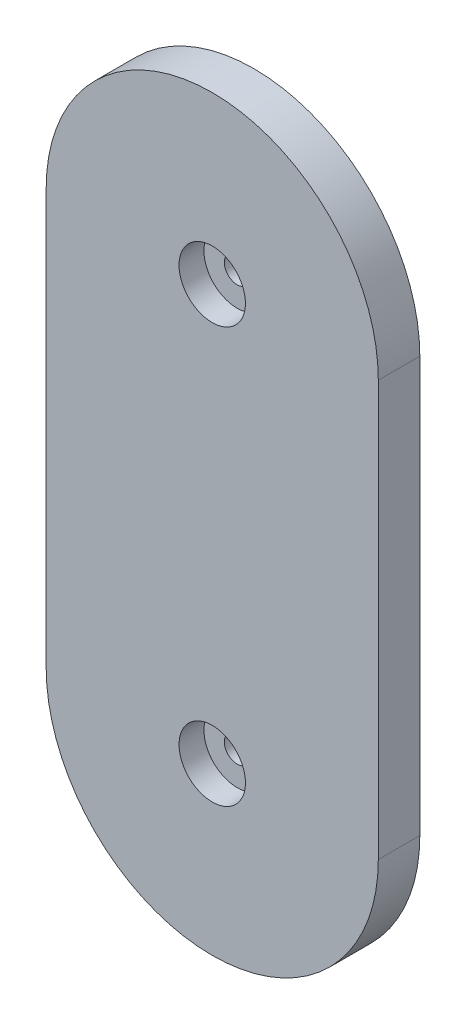
SolidWorks part; units mm, degrees
ref_plane "Front Plane" through (0, 0, 0) normal (0, 0, 1) x (1, 0, 0)
ref_plane "Top Plane" through (0, 0, 0) normal (0, 1, 0) x (1, 0, 0)
ref_plane "Right Plane" through (0, 0, 0) normal (1, 0, 0) x (0, 0, -1)
sketch "Sketch1" plane through (0, 0, 0) normal (0, 0, 1) x (1, 0, 0)
  line L0 (0, 0) -> (0, 50) construction
  line L1 (-20, 0) -> (-20, 50)
  line L2 (20, 0) -> (20, 50)
  arc A0 (-20, 0) -> (20, 0) centre (0, 0) ccw
  arc A1 (20, 50) -> (-20, 50) centre (0, 50) ccw
  point P3 (0, 25)
  dimension "D1" = 50
  dimension "D2" = 40
extrude "Boss-Extrude1" add sketch "Sketch1" along normal blind 5
sketch "Sketch3" plane through (0, 0, 5) normal (0, 0, 1) x (1, 0, 0)
  line L0 (20, 25) -> (-20, 25) construction
  line L1 (20, 0) -> (20, 50) construction
  line L2 (-20, 50) -> (-20, 0) construction
  circle A0 centre (0, 0) radius 4
  circle A1 centre (0, 50) radius 4
  dimension "D1" = 8
extrude "Cut-Extrude1" cut sketch "Sketch3" against normal blind 3
sketch "Sketch4" plane through (0, 0, 2) normal (0, 0, 1) x (1, 0, 0)
  line L0 (-20, 25) -> (20, 25) construction
  line L1 (-20, 50) -> (-20, 0) construction
  line L2 (20, 0) -> (20, 50) construction
  circle A0 centre (0, 0) radius 1.55
  circle A1 centre (0, 50) radius 1.55
  dimension "D1" = 3.1
extrude "Cut-Extrude2" cut sketch "Sketch4" against normal blind 22
